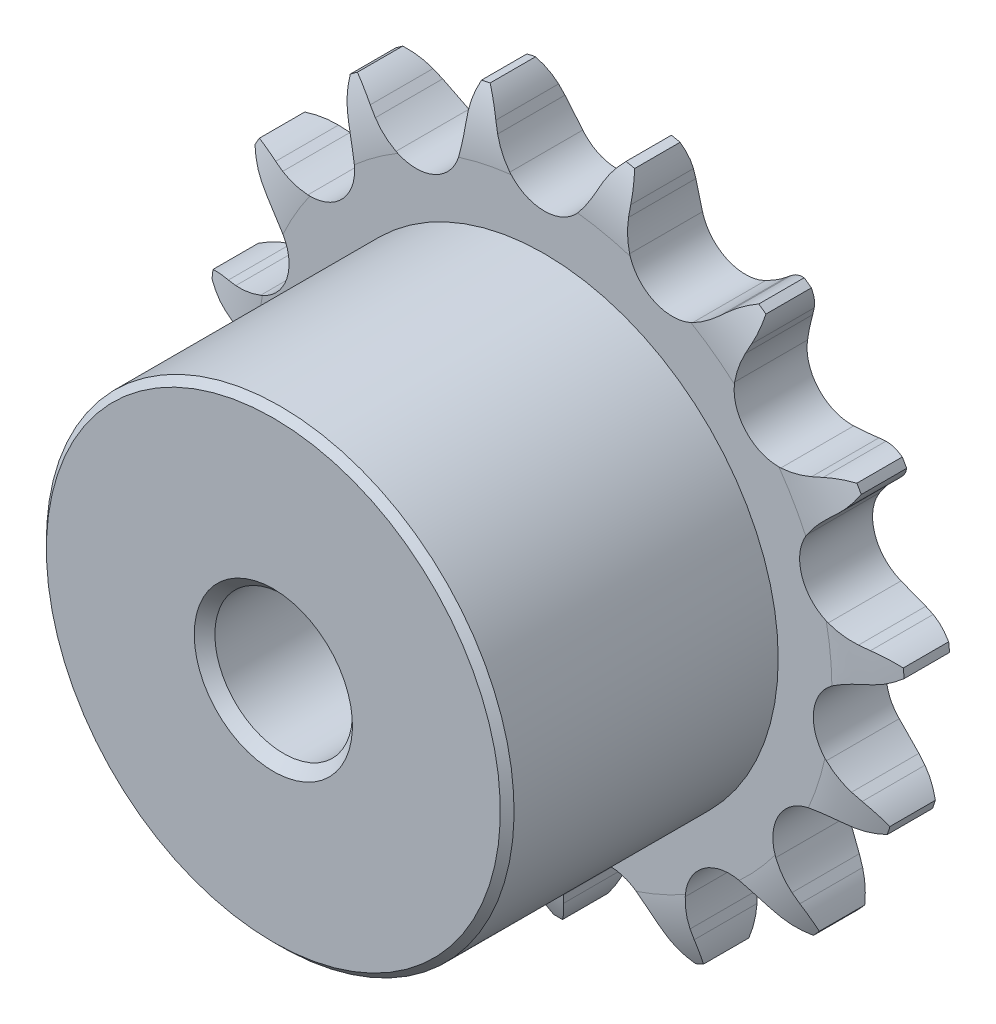
SolidWorks part; units mm, degrees
ref_plane "Front Plane" through (0, 0, 0) normal (0, 0, 1) x (1, 0, 0)
ref_plane "Top Plane" through (0, 0, 0) normal (0, 1, 0) x (1, 0, 0)
ref_plane "Right Plane" through (0, 0, 0) normal (1, 0, 0) x (0, 0, -1)
sketch "Sketch0" plane through (0, 0, 0) normal (0, 0, 1) x (1, 0, 0)
  line L0 (4.7625, -22.4058) -> (0, 0) construction
  line L1 (0, 0) -> (13.464, -18.5316) construction
  line L2 (0, 0) -> (-4.7625, -22.4058) construction
  line L3 (4.7625, -22.4058) -> (13.464, -18.5316) construction
  line L4 (4.7625, -22.4058) -> (-4.7625, -22.4058) construction
  line L5 (8.6478, -21.9513) -> (8.2246, -21.3842)
  line L6 (4.7625, -22.4058) -> (0, -23.4181) construction
  line L7 (1.0282, -23.5708) -> (1.1842, -22.8807)
  line L8 (0, -22.4058) -> (0, -25.2633) construction
  line L9 (6.7946, -19.8964) -> (1.5656, -26.3537) construction
  line L10 (0, 0) -> (0, -22.4058) construction
  line L11 (8.2246, -21.3842) -> (1.5656, -26.3537) construction
  line L12 (0, -25.2633) -> (0, -25.7077) construction
  line L13 (12.8839, -18.7899) -> (8.6478, -21.9513) construction
  circle A0 centre (0, 0) radius 25.2633 construction
  circle A1 centre (0, 0) radius 22.9064 construction
  arc A2 (-5.0851, -27.6041) -> (15.873, -23.1493) centre (0, 0) ccw
  circle A3 centre (0, 0) radius 25.7077 construction
  circle A4 centre (4.7625, -22.4058) radius 3.175 construction
  arc A7 (6.7946, -19.8964) -> (1.8855, -20.9399) centre (4.7625, -22.4058) ccw
  circle A8 centre (4.7625, -22.4058) radius 3.229 construction
  arc A9 (8.6478, -21.9513) -> (15.873, -23.1493) centre (12.8839, -18.7899) ccw
  arc A10 (8.2246, -21.3842) -> (6.7946, -19.8964) centre (1.5656, -26.3537) ccw
  arc A11 (1.0282, -23.5708) -> (-5.0851, -27.6041) centre (-4.1275, -22.4058) cw
  arc A12 (1.1842, -22.8807) -> (1.8855, -20.9399) centre (9.2888, -24.7121) cw
  dimension "D1" = 3.229
  dimension "R" = 3.229
sketch "Sketch1" plane through (0, 0, 0) normal (1, 0, 0) x (0, 0, -1)
  line L0 (2.65, 0) -> (-2.65, 0)
  line L1 (-2.65, 0) -> (-2.65, 20.9044)
  line L2 (-2.65, 22.9064) -> (0, 22.9064) construction
  line L3 (-1.65, 25.2633) -> (1.65, 25.2633)
  line L5 (2.65, 20.9044) -> (2.65, 0)
  line L7 (0, 25.2633) -> (0, 0) construction
  line L8 (-2.65, 20.9044) -> (2.65, 20.9044) construction
  line L9 (0, 25.2633) -> (0, -25.2633) construction
  line L10 (-2.65, 20.9044) -> (-2.65, 25.2633) construction
  line L11 (-2.65, 25.2633) -> (-1.65, 25.2633) construction
  line L12 (1.65, 25.2633) -> (2.65, 25.2633) construction
  line L13 (2.65, 25.2633) -> (2.65, 20.9044) construction
  line L14 (0, 0) -> (-6.4008, 0) construction
  line L15 (-2.65, 22.9064) -> (-2.65, 16.7064) construction
  line L22 (2.65, 0) -> (-22.35, 0) construction
  line L24 (-2.65, 0) -> (-2.65, 16.7064) construction
  arc A0 (-1.65, 25.2633) -> (-2.65, 20.9044) centre (7.35, 20.9044) ccw
  arc A1 (1.65, 25.2633) -> (2.65, 20.9044) centre (-7.35, 20.9044) cw
  dimension "R" = 10
sketch "Sketch6" plane through (0, 0, 0) normal (0, 0, 1) x (1, 0, 0)
  line L0 (0, 0) -> (13.464, -18.5316) construction
  line L1 (4.7625, -22.4058) -> (0, 0) construction
  line L2 (8.6478, -21.9513) -> (8.2246, -21.3842)
  line L3 (1.1842, -22.8807) -> (1.0282, -23.5708)
  line L4 (8.6478, -21.9513) -> (8.2246, -21.3842)
  line L5 (1.1842, -22.8807) -> (1.0282, -23.5708)
  line L6 (0, 0) -> (13.464, -18.5316)
  line L7 (4.7625, -22.4058) -> (0, 0)
  line L8 (0, 0) -> (0, -25.2633) construction
  line L9 (-4.7625, -22.4058) -> (4.7625, -22.4058) construction
  circle A0 centre (0, 0) radius 25.2633
  circle A1 centre (0, 0) radius 25.2633 construction
  circle A2 centre (0, 0) radius 5
  circle A3 centre (0, 0) radius 17
  circle A4 centre (0, 0) radius 10
  arc A10 (8.2246, -21.3842) -> (6.7946, -19.8964) centre (1.5656, -26.3537) ccw
  arc A11 (6.7946, -19.8964) -> (1.8855, -20.9399) centre (4.7625, -22.4058) ccw
  arc A12 (1.8855, -20.9399) -> (1.1842, -22.8807) centre (9.2888, -24.7121) ccw
  arc A13 (-5.0851, -27.6041) -> (1.0282, -23.5708) centre (-4.1275, -22.4058) ccw
  arc A14 (-5.0851, -27.6041) -> (15.873, -23.1493) centre (0, 0) ccw
  arc A15 (8.6478, -21.9513) -> (15.873, -23.1493) centre (12.8839, -18.7899) ccw
  arc A16 (8.2246, -21.3842) -> (6.7946, -19.8964) centre (1.5656, -26.3537) ccw
  arc A17 (6.7946, -19.8964) -> (1.8855, -20.9399) centre (4.7625, -22.4058) ccw
  arc A18 (1.8855, -20.9399) -> (1.1842, -22.8807) centre (9.2888, -24.7121) ccw
  arc A19 (-5.0851, -27.6041) -> (1.0282, -23.5708) centre (-4.1275, -22.4058) ccw
  arc A20 (-5.0851, -27.6041) -> (15.873, -23.1493) centre (0, 0) ccw
  arc A21 (8.6478, -21.9513) -> (15.873, -23.1493) centre (12.8839, -18.7899) ccw
  point P0 (9.3169, 20.926)
  point P13 (4.7625, -22.4058)
  point P17 (17.0227, 15.3273)
  point P28 (-4.7625, -22.4058)
  point P29 (-13.464, -18.5316)
  point P30 (-19.8375, -11.4532)
  point P31 (-22.7809, -2.3944)
  point P32 (-21.7852, 7.0785)
  point P33 (-17.0227, 15.3273)
  point P34 (-9.3169, 20.926)
  point P35 (0, 22.9064)
  point P36 (21.7852, 7.0785)
  point P37 (22.7809, -2.3944)
  point P38 (19.8375, -11.4532)
  point P39 (0, 0)
  point P40 (0, -22.4058)
  point P41 (13.464, -18.5316)
  dimension "D1" = 0
  dimension "OD" = 50.5266
  dimension "ID/For Shaft Diameter" = 10
  dimension "Hub Diameter" = 34
  dimension "D2" = 9.525
  dimension "For Maximum Shaft Diameter" = 20
  dimension "Pitch" = 9.525
  dimension "Number of Teeth" = 15
sketch "Sketch7" plane through (0, 0, 0) normal (1, 0, 0) x (0, 0, -1)
  line L1 (-22.35, 0) -> (2.65, 0)
  dimension "Overall Width" = 25
revolve "Revolve1" add sketch "Sketch1" angle 360 mid plane about L0
extrude "Cut-Extrude1" cut sketch "Sketch0" against normal through all and the other way through all
pattern_circular "CirPattern1" count 15 over 360 about axis through (0, 0, 0) along (0, 0, 1) of "Cut-Extrude1"
sketch "Sketch2" plane through (0, 0, 0) normal (0, 0, 1) x (1, 0, 0)
  circle A0 centre (0, 0) radius 5 construction
  circle A1 centre (0, 0) radius 17
  circle A2 centre (0, 0) radius 25.525 construction
  dimension "Bore" = 10
  dimension "OD" = 51.05
  dimension "Hub Dia." = 34
extrude "Boss-Extrude1" add sketch "Sketch2" along normal up to vertex (22.35 mm away) from surface at 2.65 starting at face at (0, 0, 2.65)
sketch "Sketch3" plane through (0, 0, 0) normal (0, 0, 1) x (1, 0, 0)
  circle A0 centre (0, 0) radius 5 construction
  circle A1 centre (0, 0) radius 5
extrude "Cut-Extrude2" cut sketch "Sketch3" along normal through all and the other way through all
sketch "Sketch4" plane through (0, 0, 0) normal (1, 0, 0) x (0, 0, -1)
  line L0 (-22.35, 17) -> (-22.35, 16.5)
  line L1 (-2.65, 25.2633) -> (-6.625, 25.2633) construction
  line L2 (-2.65, 25.2633) -> (-2.65, 16.7064) construction
  line L3 (-2.65, 16.7064) -> (-6.625, 16.7064) construction
  line L4 (-6.625, 25.2633) -> (-6.625, 16.7064) construction
  line L5 (2.65, 0) -> (-22.35, 0) construction
  line L6 (2.65, 0) -> (-22.35, 0) construction
  line L7 (-22.35, 5) -> (-22.35, 5.75)
  line L8 (-22.35, 17) -> (-22.35, -17) construction
  line L9 (-22.35, 16.5) -> (-21.85, 17)
  line L10 (-21.85, 17) -> (-22.35, 17)
  line L11 (-22.35, 5.75) -> (-21.6, 5)
  line L12 (2.65, 5) -> (-22.35, 5) construction
  line L13 (-21.6, 5) -> (-22.35, 5)
  line L14 (-9.85, 0) -> (-9.85, 17) construction
  line L15 (1.9, 5) -> (2.65, 5)
  line L16 (2.65, 5.75) -> (1.9, 5)
  line L17 (2.65, 5) -> (2.65, 5.75)
  line L18 (-22.35, 25.2633) -> (22.35, 25.2633)
  line L20 (0, 25.2633) -> (0, -25.2633) construction
  line L21 (-22.35, 25.2633) -> (-22.35, 69.9633)
  line L22 (-22.35, 69.9633) -> (22.35, 69.9633)
  line L23 (22.35, 69.9633) -> (22.35, 25.2633)
  point P28 (0, 25.2633)
  dimension "C" = 0.5
  dimension "D3" = 3.975
  dimension "D1" = 0.75
revolve "Cut-Revolve1" cut sketch "Sketch4" angle 360 mid plane about L22
sketch "Sketch5" plane through (0, 0, 0) normal (0, 0, 1) x (1, 0, 0)
  circle A0 centre (0, 0) radius 25.525 construction
  circle A1 centre (0, 0) radius 25.525
equation "\"360/N@Sketch0\" = 360/\"Teeth@CirPattern1\""
equation "\"Ds@Sketch0\" = 1.005 * \"Dr@Sketch0\" + ( 0.003 * 25.4 ) "
equation "\"R@Sketch0\" = 1/2 * \"Ds@Sketch0\""
equation "\"A@Sketch0\" = 35 +  ( 60 / \"Teeth@CirPattern1\" ) "
equation "\"B@Sketch0\" = 18 -  ( 56 / \"Teeth@CirPattern1\" )"
equation "\"ac@Sketch0\" = 0.8 * \"Dr@Sketch0\""
equation "\"ab@Sketch0\" = 1.4 * \"Dr@Sketch0\""
equation "\"J@Sketch0\" = 0.3 * \"Pitch@Sketch0\""
equation "\"D3@Sketch4\" = \"t@Sketch1\" * 3 / 4"
equation "\"D1@Sketch4\"=\"Bore@Sketch2\"*0.075"
